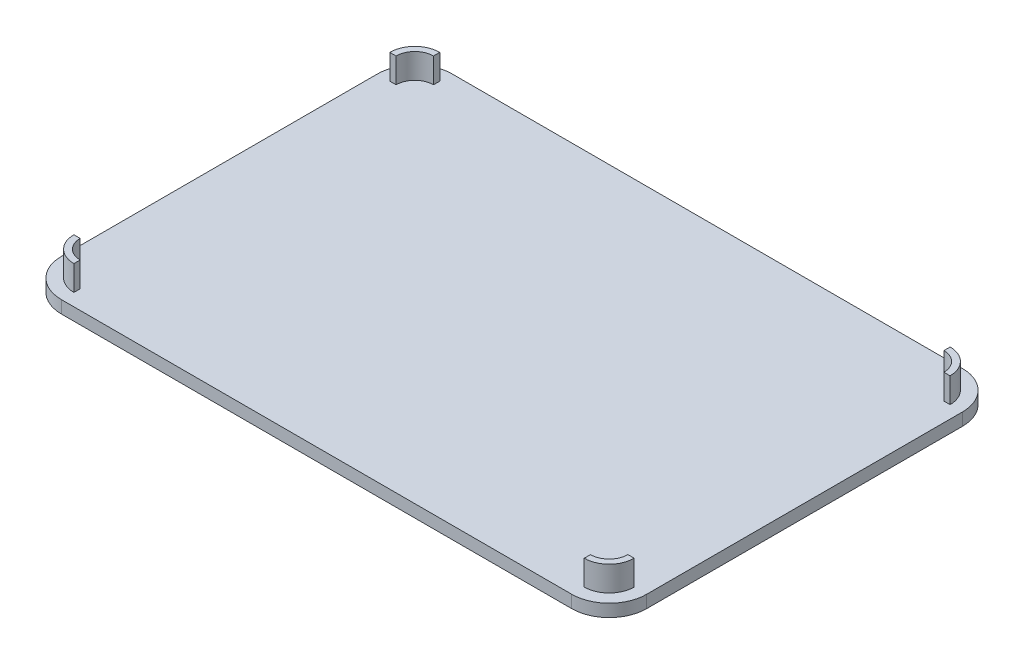
SolidWorks part; units mm, degrees
ref_plane "Alzado" through (0, 0, 0) normal (0, 0, 1) x (1, 0, 0)
ref_plane "Planta" through (0, 0, 0) normal (0, 1, 0) x (1, 0, 0)
ref_plane "Vista lateral" through (0, 0, 0) normal (1, 0, 0) x (0, 0, -1)
sketch "Croquis1" plane through (0, 0, 0) normal (0, 1, 0) x (1, 0, 0)
  line L1 (-40.87, -31.3) -> (40.87, -31.3)
  line L2 (-46.87, -25.3) -> (-46.87, 25.3)
  line L3 (-40.87, 31.3) -> (40.87, 31.3)
  line L4 (46.87, -25.3) -> (46.87, 25.3)
  line L5 (-46.87, -31.3) -> (46.87, 31.3) construction
  line L6 (-46.87, 31.3) -> (46.87, -31.3) construction
  arc A0 (40.87, -31.3) -> (46.87, -25.3) centre (40.87, -25.3) ccw
  arc A1 (40.87, 31.3) -> (46.87, 25.3) centre (40.87, 25.3) cw
  arc A2 (-46.87, 25.3) -> (-40.87, 31.3) centre (-40.87, 25.3) cw
  arc A3 (-40.87, -31.3) -> (-46.87, -25.3) centre (-40.87, -25.3) cw
  point P0 (0, 0)
  dimension "D3" = 6
  dimension "D1" = 62.6
  dimension "D2" = 93.74
extrude "Saliente-Extruir1" add sketch "Croquis1" along normal blind 2
sketch "Croquis2" plane through (0, 2, 0) normal (0, 1, 0) x (1, 0, 0)
  line L0 (-40.87, 25.3) -> (-40.87, 28.8) construction
  line L1 (-40.87, 28.8) -> (-40.87, 25.3) construction
  line L2 (-40.87, 25.3) -> (-44.37, 25.3) construction
  line L3 (-43.87, 25.3) -> (-44.87, 25.3)
  line L4 (-40.87, 29.3) -> (-40.87, 28.3)
  line L5 (0, 0) -> (-46.87, 0) construction
  line L6 (-46.87, 25.3) -> (-46.87, -25.3) construction
  line L7 (0, 0) -> (0, 31.3) construction
  line L8 (40.87, 31.3) -> (-40.87, 31.3) construction
  line L9 (-43.87, -25.3) -> (-44.87, -25.3)
  line L10 (-40.87, -29.3) -> (-40.87, -28.3)
  line L11 (43.87, 25.3) -> (44.87, 25.3)
  line L12 (40.87, 29.3) -> (40.87, 28.3)
  line L13 (43.87, -25.3) -> (44.87, -25.3)
  line L14 (40.87, -29.3) -> (40.87, -28.3)
  arc A0 (-44.37, 25.3) -> (-40.87, 28.8) centre (-40.87, 25.3) cw
  arc A1 (-43.87, 25.3) -> (-40.87, 28.3) centre (-40.87, 25.3) cw
  arc A2 (-44.87, 25.3) -> (-40.87, 29.3) centre (-40.87, 25.3) cw
  arc A3 (-44.87, -25.3) -> (-40.87, -29.3) centre (-40.87, -25.3) ccw
  arc A4 (-43.87, -25.3) -> (-40.87, -28.3) centre (-40.87, -25.3) ccw
  arc A5 (44.87, 25.3) -> (40.87, 29.3) centre (40.87, 25.3) ccw
  arc A6 (43.87, 25.3) -> (40.87, 28.3) centre (40.87, 25.3) ccw
  arc A7 (43.87, -25.3) -> (40.87, -28.3) centre (40.87, -25.3) cw
  arc A8 (44.87, -25.3) -> (40.87, -29.3) centre (40.87, -25.3) cw
  circle A13 centre (-40.87, 25.3) radius 6 construction
  circle A14 centre (-40.87, 25.3) radius 3.5 construction
  dimension "D1" = 2.5
  dimension "D2" = 0.5
  dimension "D3" = 0.5
extrude "Saliente-Extruir2" add sketch "Croquis2" along normal blind 4 contours A6 L11 A5 L12 | A2 L3 A0 L4 | L3 A1 L4 A0 | A3 L10 A4 L9 | A7 L14 A8 L13
